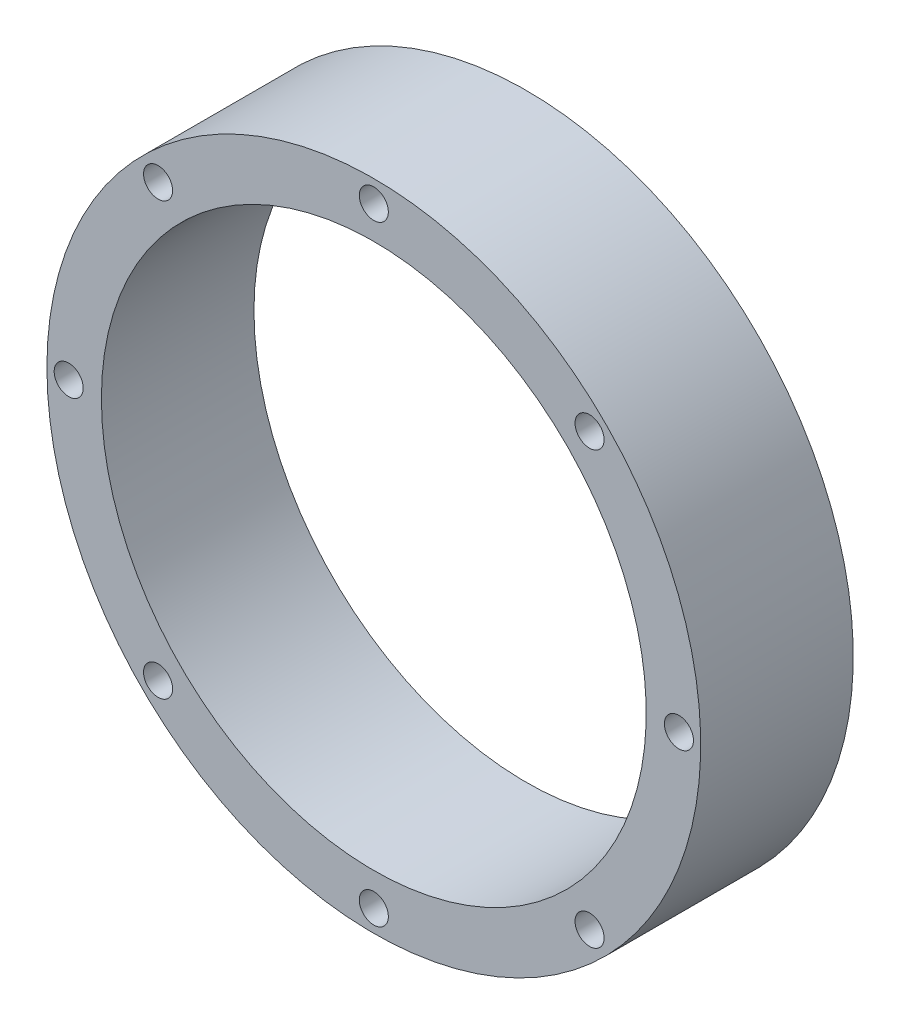
SolidWorks part; units mm, degrees
ref_plane "Front Plane" through (0, 0, 0) normal (0, 0, 1) x (1, 0, 0)
ref_plane "Top Plane" through (0, 0, 0) normal (0, 1, 0) x (1, 0, 0)
ref_plane "Right Plane" through (0, 0, 0) normal (1, 0, 0) x (0, 0, -1)
sketch "Sketch1" plane through (0, 0, 0) normal (0, 0, 1) x (1, 0, 0)
  line L0 (0, 0) -> (0, 63.1981) construction
  circle A0 centre (0, 0) radius 45
  circle A1 centre (0, 0) radius 37.5
  point P3 (0, 42)
  point P5 (29.6985, 29.6985)
  point P8 (42, 0)
  point P9 (29.6985, -29.6985)
  point P10 (0, -42)
  point P11 (-29.6985, -29.6985)
  point P12 (-42, 0)
  point P13 (-29.6985, 29.6985)
  point P14 (0, 0)
  dimension "D1" = 90
  dimension "D4" = 75
  dimension "D2" = 42
  dimension "D3" = 8
extrude "Boss-Extrude1" add sketch "Sketch1" along normal blind 21
sketch "Sketch2" plane through (0, 0, 0) normal (0, 0, 1) x (1, 0, 0)
  line L0 (0, 0) -> (0, 63.1981) construction
  circle A0 centre (0, 0) radius 45
  point P3 (0, 42)
  point P5 (29.6985, 29.6985)
  point P8 (42, 0)
  point P9 (29.6985, -29.6985)
  point P10 (0, -42)
  point P11 (-29.6985, -29.6985)
  point P12 (-42, 0)
  point P13 (-29.6985, 29.6985)
  point P14 (0, 0)
  dimension "D1" = 90
  dimension "D2" = 42
  dimension "D3" = 8
hole_wizard "Ø4.0mm Dowel Hole1" positions "Sketch3" profile "Sketch4" hole size "Ø4.0" standard "ISO" end condition through all
sketch "Sketch3" plane through (0, 0, 0) normal (0, 0, -1) x (-1, 0, 0)
  point P0 (29.6985, 29.6985)
  point P3 (0, 42)
  point P6 (-29.6985, 29.6985)
  point P9 (-42, 0)
  point P12 (-29.6985, -29.6985)
  point P15 (0, -42)
  point P18 (29.6985, -29.6985)
  point P21 (42, 0)
sketch "Sketch4" plane through (-29.6985, 29.6985, 0) normal (1, 0, 0) x (0, 1, 0)
  line L0 (0, 0) -> (0, 21)
  line L1 (0, 21) -> (2, 21)
  line L2 (2, 21) -> (2, 0.025)
  line L3 (2, 0.025) -> (2.025, 0)
  line L5 (2.025, 0) -> (0, 0)
  line L6 (-2, 0.025) -> (-2.025, 0) construction
  line L11 (0, -6.35) -> (0, 107.95) construction
  dimension "Thru Hole Dia." = 4
  dimension "Thru Hole Depth" = 21
  dimension "Near C'Sink Dia." = 4.05
  dimension "Near C'Sink Angle" = 90
